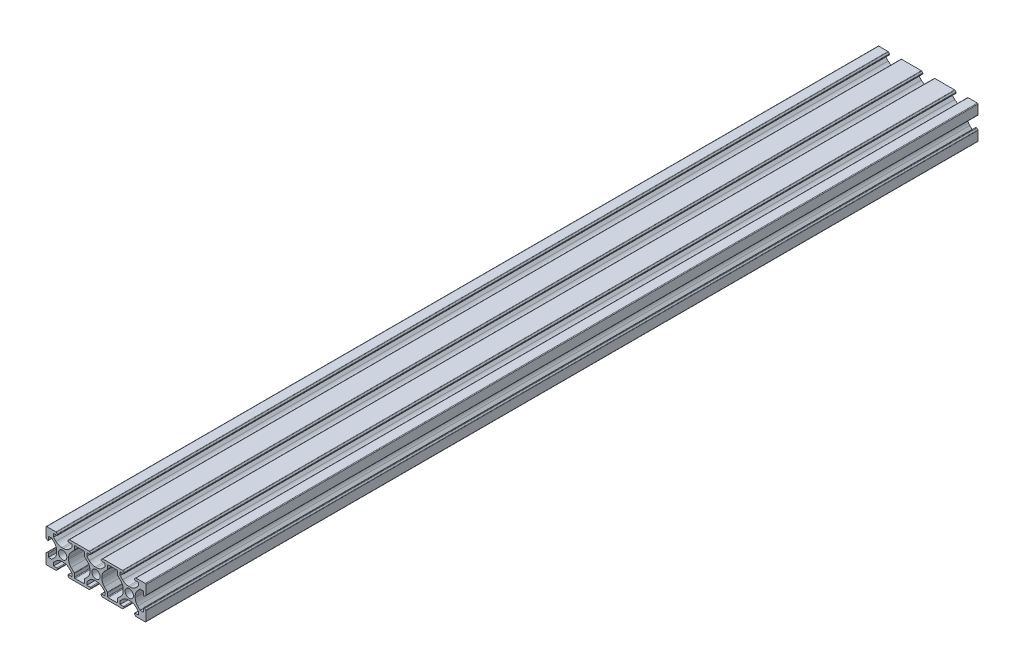
SolidWorks part; units mm, degrees
ref_plane "Plano frontal" through (0, 0, 0) normal (0, 0, 1) x (1, 0, 0)
ref_plane "Plano superior" through (0, 0, 0) normal (0, 1, 0) x (1, 0, 0)
ref_plane "Plano direito" through (0, 0, 0) normal (1, 0, 0) x (0, 0, -1)
sketch "Esboço1" plane through (0, 0, 0) normal (0, 0, 1) x (1, 0, 0)
  line L0 (-9.0343, 3.1) -> (-8.9, 3.1)
  line L3 (-10, 10) -> (-4.0657, 10)
  line L5 (-10, -10) -> (10, 10) construction
  line L6 (-10, 10) -> (10, -10) construction
  line L7 (-8.5, 3.5) -> (-8.5, 5.5)
  line L8 (-10, 0) -> (10, 0) construction
  line L9 (0, 10) -> (0, -10) construction
  line L12 (-8.5, 5.5) -> (-6.5607, 5.5)
  line L15 (-6.5607, 5.5) -> (-5.0645, 4.0038)
  line L16 (-3.6, 0.4683) -> (-3.6, 0)
  line L17 (-0.4683, 3.6) -> (0, 3.6)
  line L18 (-5.5, 6.5607) -> (-4.0038, 5.0645)
  line L21 (-5.5, 8.5) -> (-5.5, 6.5607)
  line L24 (-3.5, 8.5) -> (-5.5, 8.5)
  line L25 (-3.1, 9.0343) -> (-3.1, 8.9)
  line L44 (-10, 4.0657) -> (-10, 10)
  line L45 (-9.8828, 3.7828) -> (-9.3172, 3.2172)
  line L46 (-3.7828, 9.8828) -> (-3.2172, 9.3172)
  line L47 (-3.6, 0) -> (-2.5, 0)
  line L48 (0, 3.6) -> (0, 2.5)
  arc A0 (-3.5, 8.5) -> (-3.1, 8.9) centre (-3.5, 8.9) ccw
  arc A1 (-3.7828, 9.8828) -> (-4.0657, 10) centre (-4.0657, 9.6) ccw
  arc A2 (-10, 4.0657) -> (-9.8828, 3.7828) centre (-9.6, 4.0657) ccw
  arc A3 (-8.5, 3.5) -> (-8.9, 3.1) centre (-8.9, 3.5) cw
  arc A4 (-3.2172, 9.3172) -> (-3.1, 9.0343) centre (-3.5, 9.0343) cw
  arc A5 (-9.3172, 3.2172) -> (-9.0343, 3.1) centre (-9.0343, 3.5) ccw
  arc A6 (-3.6, 0.4683) -> (-5.0645, 4.0038) centre (-8.6, 0.4683) ccw
  arc A7 (-4.0038, 5.0645) -> (-0.4683, 3.6) centre (-0.4683, 8.6) ccw
  circle A8 centre (0, 0) radius 2.5
  point P6 (-10, 3.1)
  point P28 (-3.1, 8.5)
  point P31 (-3.1, 10)
  point P33 (-3.9, 10)
  point P36 (-10, 3.9)
  point P39 (-8.5, 3.1)
  point P42 (-3.1, 9.2)
  point P45 (-9.2, 3.1)
  point P48 (-3.6, 2.5393)
  point P51 (-2.5393, 3.6)
  dimension "D5" = 10
  dimension "D9" = 0.4
  dimension "D10" = 0.4
  dimension "D11" = 5
  dimension "D12" = 5
  dimension "D13" = 5
  dimension "D1" = 6.9
  dimension "D2" = 1.5
  dimension "D3" = 3.6
  dimension "D4" = 1.5
  dimension "D6" = 2.4
  dimension "D7" = 3.6
  dimension "D8" = 45
extrude "Ressalto-extrusão1" add sketch "Esboço1" along normal blind 500
sketch "Esboço3" plane through (0, 0, 0) normal (1, 0, 0) x (0, 0, -1)
  line L0 (0, 0) -> (-1000, 0) construction
  dimension "D1" = 1000
pattern_circular "PadrãoCircular1" count 4 over 360 about axis through (0, 0, 0) along (0, 0, 1) of "Ressalto-extrusão1"
pattern_linear "Padrão linear1" count 3 spacing 20 along (1, 0, 0) of "Ressalto-extrusão1", "PadrãoCircular1"
sketch "Esboço4" plane through (0, 0, 0) normal (0, 0, -1) x (-1, 0, 0)
  line L0 (-13.4393, 5.5) -> (-13, 5.9393)
  line L1 (-13, 8.5) -> (-13, 5.9393)
  line L2 (-10, 10) -> (-10, -10) construction
  line L3 (-4.0657, 10) -> (-15.9343, 10) construction
  line L4 (-15.9343, -10) -> (-4.0657, -10) construction
  line L5 (-11.5, 5.5) -> (-13.4393, 5.5) construction
  line L6 (-14.5, 8.5) -> (-14.5, 6.5607) construction
  line L7 (-7, 8.5) -> (-7, 5.9393)
  line L8 (-6.5607, 5.5) -> (-7, 5.9393)
  line L9 (-13, 8.5) -> (-7, 8.5)
  line L10 (-20, 0) -> (0, 0) construction
  line L11 (-13, -8.5) -> (-7, -8.5)
  line L12 (-6.5607, -5.5) -> (-7, -5.9393)
  line L13 (-7, -8.5) -> (-7, -5.9393)
  line L14 (-13, -8.5) -> (-13, -5.9393)
  line L15 (-13.4393, -5.5) -> (-13, -5.9393)
  line L16 (-13.4393, 5.5) -> (-13.4393, -5.5)
  line L17 (-6.5607, -5.5) -> (-6.5607, 5.5)
  line L31 (-40, 0) -> (-20, 0) construction
  line L32 (-33.4393, 5.5) -> (-33, 5.9393) [skipped]
  line L33 (-33, 8.5) -> (-33, 5.9393) [skipped]
  line L34 (-27, 8.5) -> (-27, 5.9393) [skipped]
  line L35 (-26.5607, 5.5) -> (-27, 5.9393) [skipped]
  line L36 (-33, 8.5) -> (-27, 8.5) [skipped]
  line L37 (-33, -8.5) -> (-27, -8.5) [skipped]
  line L38 (-26.5607, -5.5) -> (-27, -5.9393) [skipped]
  line L39 (-27, -8.5) -> (-27, -5.9393) [skipped]
  line L40 (-33, -8.5) -> (-33, -5.9393) [skipped]
  line L41 (-33.4393, -5.5) -> (-33, -5.9393) [skipped]
  line L42 (-33.4393, 5.5) -> (-33.4393, -5.5) [skipped]
  line L43 (-26.5607, -5.5) -> (-26.5607, 5.5) [skipped]
  line L44 (-30, 10) -> (-30, -10) construction
  dimension "D1" = 45
  dimension "D2" = 1.5
  dimension "D3" = 1.5
  dimension "D4" = 2
extrude "Corte-extrusão1" cut sketch "Esboço4" against normal through all
pattern_linear "Padrão linear2" count 2 spacing 20 along (1, 0, 0) of "Corte-extrusão1"
fillet "Filete1" radius 0.4 16 edges at (13, -5.9393, 250) (13, -8.5, 250) (7, -8.5, 250) (7, -5.9393, 250) (7, 8.5, 250) (7, 5.9393, 250) (13, 8.5, 250) (13, 5.9393, 250) (27, -8.5, 250) (27, -5.9393, 250) (27, 8.5, 250) (27, 5.9393, 250) (33, 8.5, 250) (33, -8.5, 250) (33, -5.9393, 250) (33, 5.9393, 250)
fillet "Filete2" radius 0.4 4 edges at (-10, 10, 250) (50, -10, 250) (50, 10, 250) (-10, -10, 250)
